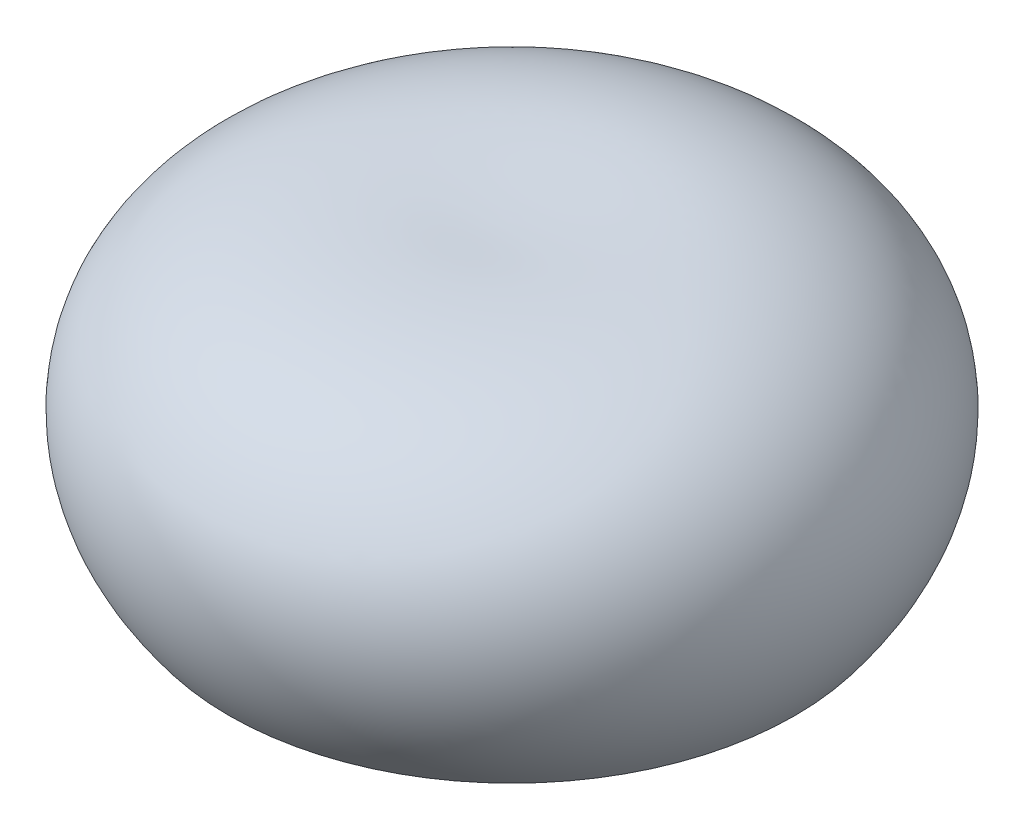
SolidWorks part; units mm, degrees
ref_plane "前视基准面" through (0, 0, 0) normal (0, 0, 1) x (1, 0, 0)
ref_plane "上视基准面" through (0, 0, 0) normal (0, 1, 0) x (1, 0, 0)
ref_plane "右视基准面" through (0, 0, 0) normal (1, 0, 0) x (0, 0, -1)
curve "曲线1"
  spline degree 3 poles (0, 7, 0) (0.0738, 6.9996, 0) (0.1783, 6.9991, 0) (0.3064, 7.0012, 0) (0.3805, 7.0029, 0) (0.4416, 7.0045, 0) (0.495, 7.0061, 0) (0.5432, 7.0077, 0) (0.5875, 7.0093, 0) (0.6288, 7.0109, 0) (0.6676, 7.0125, 0) (0.7044, 7.0141, 0) (0.7394, 7.0157, 0) (0.7729, 7.0172, 0) (0.8051, 7.0187, 0) (0.8362, 7.0203, 0) (0.8662, 7.0218, 0) (0.8953, 7.0233, 0) (0.9235, 7.0247, 0) (0.951, 7.0262, 0) (0.9778, 7.0276, 0) (1.004, 7.0291, 0) (1.0295, 7.0305, 0) (1.0545, 7.0319, 0) (1.079, 7.0333, 0) (1.103, 7.0346, 0) (1.1265, 7.036, 0) (1.1496, 7.0373, 0) (1.1724, 7.0386, 0) (1.1947, 7.0399, 0) (1.2167, 7.0412, 0) (1.2384, 7.0425, 0) (1.2598, 7.0438, 0) (1.2808, 7.045, 0) (1.3016, 7.0462, 0) (1.3221, 7.0474, 0) (1.3423, 7.0486, 0) (1.3623, 7.0498, 0) (1.382, 7.051, 0) (1.4015, 7.0521, 0) (1.4208, 7.0533, 0) (1.4399, 7.0544, 0) (1.4588, 7.0555, 0) (1.4775, 7.0566, 0) (1.496, 7.0577, 0) (1.5143, 7.0587, 0) (1.5324, 7.0598, 0) (1.5504, 7.0608, 0) (1.5682, 7.0618, 0) (1.5859, 7.0628, 0) (1.6034, 7.0638, 0) (1.6207, 7.0648, 0) (1.6379, 7.0657, 0) (1.655, 7.0667, 0) (1.672, 7.0676, 0) (1.6888, 7.0685, 0) (1.7054, 7.0694, 0) (1.722, 7.0703, 0) (1.7385, 7.0712, 0) (1.7548, 7.072, 0) (1.771, 7.0728, 0) (1.7871, 7.0737, 0) (1.8031, 7.0745, 0) (1.819, 7.0753, 0) (1.8348, 7.0761, 0) (1.8505, 7.0768, 0) (1.8661, 7.0776, 0) (1.8816, 7.0783, 0) (1.897, 7.079, 0) (1.9123, 7.0797, 0) (1.9275, 7.0804, 0) (1.9427, 7.0811, 0) (1.9578, 7.0818, 0) (1.9727, 7.0824, 0) (1.9876, 7.0831, 0) (2.0025, 7.0837, 0) (2.0172, 7.0843, 0) (2.0319, 7.0849, 0) (2.0465, 7.0855, 0) (2.061, 7.0861, 0) (2.0755, 7.0866, 0) (2.0899, 7.0872, 0) (2.1042, 7.0877, 0) (2.1184, 7.0882, 0) (2.1326, 7.0887, 0) (2.1468, 7.0892, 0) (2.1608, 7.0896, 0) (2.1748, 7.0901, 0) (2.1888, 7.0905, 0) (2.2027, 7.091, 0) (2.2165, 7.0914, 0) (2.2302, 7.0918, 0) (2.244, 7.0922, 0) (2.2576, 7.0925, 0) (2.2712, 7.0929, 0) (2.2848, 7.0933, 0) (2.2983, 7.0936, 0) (2.3117, 7.0939, 0) (2.3251, 7.0942, 0) (2.3385, 7.0945, 0) (2.3518, 7.0948, 0) (2.365, 7.095, 0) (2.3782, 7.0953, 0) (2.3914, 7.0955, 0) (2.4045, 7.0958, 0) (2.4175, 7.096, 0) (2.4305, 7.0962, 0) (2.4435, 7.0964, 0) (2.4565, 7.0965, 0) (2.4693, 7.0967, 0) (2.4822, 7.0968, 0) (2.495, 7.097, 0) (2.5078, 7.0971, 0) (2.5205, 7.0972, 0) (2.5332, 7.0973, 0) (2.5458, 7.0974, 0) (2.5584, 7.0974, 0) (2.571, 7.0975, 0) (2.5835, 7.0975, 0) (2.596, 7.0975, 0) (2.6085, 7.0975, 0) (2.6209, 7.0975, 0) (2.6333, 7.0975, 0) (2.6457, 7.0975, 0) (2.658, 7.0975, 0) (2.6703, 7.0974, 0) (2.6825, 7.0973, 0) (2.6948, 7.0973, 0) (2.7069, 7.0972, 0) (2.7191, 7.0971, 0) (2.7312, 7.0969, 0) (2.7433, 7.0968, 0) (2.7554, 7.0967, 0) (2.7674, 7.0965, 0) (2.7794, 7.0963, 0) (2.7914, 7.0962, 0) (2.8033, 7.096, 0) (2.8152, 7.0958, 0) (2.8271, 7.0955, 0) (2.8389, 7.0953, 0) (2.8508, 7.095, 0) (2.8625, 7.0948, 0) (2.8743, 7.0945, 0) (2.8861, 7.0942, 0) (2.8978, 7.0939, 0) (2.9094, 7.0936, 0) (2.9211, 7.0933, 0) (2.9327, 7.093, 0) (2.9443, 7.0926, 0) (2.9559, 7.0922, 0) (2.9675, 7.0919, 0) (2.979, 7.0915, 0) (2.9905, 7.0911, 0) (3.002, 7.0907, 0) (3.0134, 7.0902, 0) (3.0249, 7.0898, 0) (3.0363, 7.0893, 0) (3.0477, 7.0889, 0) (3.059, 7.0884, 0) (3.0704, 7.0879, 0) (3.0817, 7.0874, 0) (3.093, 7.0869, 0) (3.1042, 7.0864, 0) (3.1155, 7.0858, 0) (3.1267, 7.0853, 0) (3.1379, 7.0847, 0) (3.1491, 7.0841, 0) (3.1602, 7.0835, 0) (3.1714, 7.0829, 0) (3.1825, 7.0823, 0) (3.1936, 7.0817, 0) (3.2047, 7.0811, 0) (3.2157, 7.0804, 0) (3.2267, 7.0797, 0) (3.2378, 7.0791, 0) (3.2488, 7.0784, 0) (3.2597, 7.0777, 0) (3.2707, 7.0769, 0) (3.2816, 7.0762, 0) (3.2925, 7.0755, 0) (3.3034, 7.0747, 0) (3.3143, 7.074, 0) (3.3252, 7.0732, 0) (3.336, 7.0724, 0) (3.3468, 7.0716, 0) (3.3576, 7.0708, 0) (3.3684, 7.0699, 0) (3.3792, 7.0691, 0) (3.3899, 7.0683, 0) (3.4006, 7.0674, 0) (3.4113, 7.0665, 0) (3.422, 7.0656, 0) (3.4327, 7.0647, 0) (3.4434, 7.0638, 0) (3.454, 7.0629, 0) (3.4646, 7.0619, 0) (3.4752, 7.061, 0) (3.4858, 7.06, 0) (3.4964, 7.059, 0) (3.507, 7.0581, 0) (3.5175, 7.0571, 0) (3.528, 7.056, 0) (3.5385, 7.055, 0) (3.549, 7.054, 0) (3.5595, 7.0529, 0) (3.5699, 7.0519, 0) (3.5804, 7.0508, 0) (3.5908, 7.0497, 0) (3.6012, 7.0486, 0) (3.6116, 7.0475, 0) (3.622, 7.0464, 0) (3.6324, 7.0452, 0) (3.6427, 7.0441, 0) (3.6531, 7.0429, 0) (3.6634, 7.0417, 0) (3.6737, 7.0406, 0) (3.684, 7.0394, 0) (3.6942, 7.0381, 0) (3.7045, 7.0369, 0) (3.7148, 7.0357, 0) (3.725, 7.0344, 0) (3.7352, 7.0332, 0) (3.7454, 7.0319, 0) (3.7556, 7.0306, 0) (3.7658, 7.0293, 0) (3.7759, 7.028, 0) (3.7861, 7.0267, 0) (3.7962, 7.0254, 0) (3.8063, 7.024, 0) (3.8164, 7.0227, 0) (3.8265, 7.0213, 0) (3.8366, 7.0199, 0) (3.8467, 7.0185, 0) (3.8567, 7.0171, 0) (3.8668, 7.0157, 0) (3.8768, 7.0142, 0) (3.8868, 7.0128, 0) (3.8968, 7.0113, 0) (3.9068, 7.0099, 0) (3.9168, 7.0084, 0) (3.9267, 7.0069, 0) (3.9367, 7.0054, 0) (3.9466, 7.0039, 0) (3.9565, 7.0024, 0) (3.9665, 7.0008, 0) (3.9764, 6.9993, 0) (3.9862, 6.9977, 0) (3.9961, 6.9961, 0) (4.006, 6.9945, 0) (4.0158, 6.9929, 0) (4.0257, 6.9913, 0) (4.0355, 6.9897, 0) (4.0453, 6.988, 0) (4.0551, 6.9864, 0) (4.0649, 6.9847, 0) (4.0747, 6.983, 0) (4.0844, 6.9813, 0) (4.0942, 6.9796, 0) (4.1039, 6.9779, 0) (4.1136, 6.9762, 0) (4.1234, 6.9745, 0) (4.1331, 6.9727, 0) (4.1428, 6.971, 0) (4.1524, 6.9692, 0) (4.1621, 6.9674, 0) (4.1718, 6.9656, 0) (4.1814, 6.9638, 0) (4.1911, 6.962, 0) (4.2007, 6.9601, 0) (4.2103, 6.9583, 0) (4.2199, 6.9564, 0) (4.2295, 6.9545, 0) (4.2391, 6.9527, 0) (4.2486, 6.9508, 0) (4.2582, 6.9488, 0) (4.2677, 6.9469, 0) (4.2773, 6.945, 0) (4.2868, 6.943, 0) (4.2963, 6.9411, 0) (4.3058, 6.9391, 0) (4.3153, 6.9371, 0) (4.3248, 6.9351, 0) (4.3343, 6.9331, 0) (4.3437, 6.9311, 0) (4.3532, 6.9291, 0) (4.3626, 6.927, 0) (4.3721, 6.925, 0) (4.3815, 6.9229, 0) (4.3909, 6.9208, 0) (4.4003, 6.9187, 0) (4.4097, 6.9166, 0) (4.4191, 6.9145, 0) (4.4284, 6.9123, 0) (4.4378, 6.9102, 0) (4.4471, 6.908, 0) (4.4565, 6.9059, 0) (4.4658, 6.9037, 0) (4.4751, 6.9015, 0) (4.4844, 6.8993, 0) (4.4937, 6.8971, 0) (4.503, 6.8948, 0) (4.5123, 6.8926, 0) (4.5215, 6.8903, 0) (4.5308, 6.8881, 0) (4.54, 6.8858, 0) (4.5493, 6.8835, 0) (4.5585, 6.8812, 0) (4.5677, 6.8789, 0) (4.5769, 6.8765, 0) (4.5861, 6.8742, 0) (4.5953, 6.8718, 0) (4.6045, 6.8695, 0) (4.6136, 6.8671, 0) (4.6228, 6.8647, 0) (4.6319, 6.8623, 0) (4.6411, 6.8599, 0) (4.6502, 6.8575, 0) (4.6593, 6.855, 0) (4.6684, 6.8526, 0) (4.6775, 6.8501, 0) (4.6866, 6.8476, 0) (4.6957, 6.8451, 0) (4.7048, 6.8426, 0) (4.7138, 6.8401, 0) (4.7229, 6.8376, 0) (4.7319, 6.835, 0) (4.741, 6.8325, 0) (4.75, 6.8299, 0) (4.759, 6.8273, 0) (4.768, 6.8247, 0) (4.777, 6.8221, 0) (4.786, 6.8195, 0) (4.795, 6.8169, 0) (4.8039, 6.8142, 0) (4.8129, 6.8116, 0) (4.8218, 6.8089, 0) (4.8308, 6.8062, 0) (4.8397, 6.8035, 0) (4.8486, 6.8008, 0) (4.8575, 6.7981, 0) (4.8664, 6.7954, 0) (4.8753, 6.7926, 0) (4.8842, 6.7899, 0) (4.8931, 6.7871, 0) (4.902, 6.7843, 0) (4.9108, 6.7815, 0) (4.9197, 6.7787, 0) (4.9285, 6.7759, 0) (4.9373, 6.7731, 0) (4.9462, 6.7702, 0) (4.955, 6.7673, 0) (4.9638, 6.7645, 0) (4.9726, 6.7616, 0) (4.9813, 6.7587, 0) (4.9901, 6.7558, 0) (4.9989, 6.7529, 0) (5.0076, 6.7499, 0) (5.0164, 6.747, 0) (5.0251, 6.744, 0) (5.0339, 6.7411, 0) (5.0426, 6.7381, 0) (5.0513, 6.7351, 0) (5.06, 6.7321, 0) (5.0687, 6.729, 0) (5.0774, 6.726, 0) (5.0861, 6.7229, 0) (5.0947, 6.7199, 0) (5.1034, 6.7168, 0) (5.112, 6.7137, 0) (5.1207, 6.7106, 0) (5.1293, 6.7075, 0) (5.1379, 6.7044, 0) (5.1465, 6.7012, 0) (5.1552, 6.6981, 0) (5.1638, 6.6949, 0) (5.1723, 6.6917, 0) (5.1809, 6.6885, 0) (5.1895, 6.6853, 0) (5.1981, 6.6821, 0) (5.2066, 6.6789, 0) (5.2151, 6.6756, 0) (5.2237, 6.6724, 0) (5.2322, 6.6691, 0) (5.2407, 6.6658, 0) (5.2492, 6.6625, 0) (5.2577, 6.6592, 0) (5.2662, 6.6559, 0) (5.2747, 6.6526, 0) (5.2832, 6.6492, 0) (5.2917, 6.6459, 0) (5.3001, 6.6425, 0) (5.3086, 6.6391, 0) (5.317, 6.6357, 0) (5.3254, 6.6323, 0) (5.3338, 6.6289, 0) (5.3423, 6.6254, 0) (5.3507, 6.622, 0) (5.3591, 6.6185, 0) (5.3674, 6.615, 0) (5.3758, 6.6115, 0) (5.3842, 6.608, 0) (5.3926, 6.6045, 0) (5.4009, 6.601, 0) (5.4092, 6.5974, 0) (5.4176, 6.5939, 0) (5.4259, 6.5903, 0) (5.4342, 6.5867, 0) (5.4425, 6.5831, 0) (5.4508, 6.5795, 0) (5.4591, 6.5759, 0) (5.4674, 6.5722, 0) (5.4757, 6.5686, 0) (5.4839, 6.5649, 0) (5.4922, 6.5612, 0) (5.5004, 6.5576, 0) (5.5087, 6.5538, 0) (5.5169, 6.5501, 0) (5.5251, 6.5464, 0) (5.5333, 6.5427, 0) (5.5415, 6.5389, 0) (5.5497, 6.5351, 0) (5.5579, 6.5313, 0) (5.5661, 6.5275, 0) (5.5743, 6.5237, 0) (5.5824, 6.5199, 0) (5.5906, 6.5161, 0) (5.5987, 6.5122, 0) (5.6069, 6.5083, 0) (5.615, 6.5045, 0) (5.6231, 6.5006, 0) (5.6312, 6.4967, 0) (5.6393, 6.4927, 0) (5.6474, 6.4888, 0) (5.6555, 6.4849, 0) (5.6635, 6.4809, 0) (5.6716, 6.4769, 0) (5.6796, 6.4729, 0) (5.6877, 6.4689, 0) (5.6957, 6.4649, 0) (5.7038, 6.4609, 0) (5.7118, 6.4568, 0) (5.7198, 6.4528, 0) (5.7278, 6.4487, 0) (5.7358, 6.4446, 0) (5.7438, 6.4405, 0) (5.7517, 6.4364, 0) (5.7597, 6.4323, 0) (5.7676, 6.4282, 0) (5.7756, 6.424, 0) (5.7835, 6.4198, 0) (5.7915, 6.4157, 0) (5.7994, 6.4115, 0) (5.8073, 6.4073, 0) (5.8152, 6.403, 0) (5.8231, 6.3988, 0) (5.831, 6.3945, 0) (5.8388, 6.3903, 0) (5.8467, 6.386, 0) (5.8546, 6.3817, 0) (5.8624, 6.3774, 0) (5.8703, 6.3731, 0) (5.8781, 6.3687, 0) (5.8859, 6.3644, 0) (5.8937, 6.36, 0) (5.9015, 6.3557, 0) (5.9093, 6.3513, 0) (5.9171, 6.3469, 0) (5.9249, 6.3424, 0) (5.9326, 6.338, 0) (5.9404, 6.3336, 0) (5.9481, 6.3291, 0) (5.9559, 6.3246, 0) (5.9636, 6.3201, 0) (5.9713, 6.3156, 0) (5.979, 6.3111, 0) (5.9867, 6.3066, 0) (5.9944, 6.302, 0) (6.0021, 6.2975, 0) (6.0098, 6.2929, 0) (6.0175, 6.2883, 0) (6.0251, 6.2837, 0) (6.0328, 6.2791, 0) (6.0404, 6.2745, 0) (6.048, 6.2698, 0) (6.0556, 6.2652, 0) (6.0633, 6.2605, 0) (6.0709, 6.2558, 0) (6.0784, 6.2511, 0) (6.086, 6.2464, 0) (6.0936, 6.2416, 0) (6.1012, 6.2369, 0) (6.1087, 6.2321, 0) (6.1163, 6.2274, 0) (6.1238, 6.2226, 0) (6.1313, 6.2178, 0) (6.1388, 6.2129, 0) (6.1463, 6.2081, 0) (6.1538, 6.2033, 0) (6.1613, 6.1984, 0) (6.1688, 6.1935, 0) (6.1763, 6.1886, 0) (6.1837, 6.1837, 0) (6.1912, 6.1788, 0) (6.1986, 6.1739, 0) (6.206, 6.1689, 0) (6.2134, 6.1639, 0) (6.2208, 6.159, 0) (6.2282, 6.154, 0) (6.2356, 6.1489, 0) (6.243, 6.1439, 0) (6.2504, 6.1389, 0) (6.2577, 6.1338, 0) (6.2651, 6.1287, 0) (6.2724, 6.1237, 0) (6.2798, 6.1186, 0) (6.2871, 6.1134, 0) (6.2944, 6.1083, 0) (6.3017, 6.1032, 0) (6.309, 6.098, 0) (6.3163, 6.0928, 0) (6.3235, 6.0876, 0) (6.3308, 6.0824, 0) (6.3381, 6.0772, 0) (6.3453, 6.072, 0) (6.3525, 6.0667, 0) (6.3598, 6.0615, 0) (6.367, 6.0562, 0) (6.3742, 6.0509, 0) (6.3814, 6.0456, 0) (6.3885, 6.0403, 0) (6.3957, 6.0349, 0) (6.4029, 6.0296, 0) (6.41, 6.0242, 0) (6.4172, 6.0188, 0) (6.4243, 6.0134, 0) (6.4314, 6.008, 0) (6.4385, 6.0025, 0) (6.4456, 5.9971, 0) (6.4527, 5.9916, 0) (6.4598, 5.9861, 0) (6.4668, 5.9806, 0) (6.4739, 5.9751, 0) (6.4809, 5.9696, 0) (6.488, 5.9641, 0) (6.495, 5.9585, 0) (6.502, 5.9529, 0) (6.509, 5.9473, 0) (6.516, 5.9417, 0) (6.523, 5.9361, 0) (6.53, 5.9305, 0) (6.5369, 5.9248, 0) (6.5439, 5.9192, 0) (6.5508, 5.9135, 0) (6.5578, 5.9078, 0) (6.5647, 5.9021, 0) (6.5716, 5.8963, 0) (6.5785, 5.8906, 0) (6.5854, 5.8848, 0) (6.5922, 5.8791, 0) (6.5991, 5.8733, 0) (6.606, 5.8675, 0) (6.6128, 5.8616, 0) (6.6196, 5.8558, 0) (6.6265, 5.8499, 0) (6.6333, 5.8441, 0) (6.6401, 5.8382, 0) (6.6469, 5.8323, 0) (6.6536, 5.8263, 0) (6.6604, 5.8204, 0) (6.6672, 5.8144, 0) (6.6739, 5.8085, 0) (6.6806, 5.8025, 0) (6.6874, 5.7965, 0) (6.6941, 5.7905, 0) (6.7008, 5.7844, 0) (6.7074, 5.7784, 0) (6.7141, 5.7723, 0) (6.7208, 5.7662, 0) (6.7274, 5.7601, 0) (6.7341, 5.754, 0) (6.7407, 5.7479, 0) (6.7473, 5.7417, 0) (6.7539, 5.7356, 0) (6.7605, 5.7294, 0) (6.7671, 5.7232, 0) (6.7737, 5.717, 0) (6.7802, 5.7107, 0) (6.7868, 5.7045, 0) (6.7933, 5.6982, 0) (6.7998, 5.6919, 0) (6.8064, 5.6856, 0) (6.8129, 5.6793, 0) (6.8194, 5.673, 0) (6.8258, 5.6666, 0) (6.8323, 5.6603, 0) (6.8387, 5.6539, 0) (6.8452, 5.6475, 0) (6.8516, 5.6411, 0) (6.858, 5.6346, 0) (6.8644, 5.6282, 0) (6.8708, 5.6217, 0) (6.8772, 5.6152, 0) (6.8836, 5.6087, 0) (6.8899, 5.6022, 0) (6.8963, 5.5957, 0) (6.9026, 5.5891, 0) (6.9089, 5.5825, 0) (6.9152, 5.5759, 0) (6.9215, 5.5693, 0) (6.9278, 5.5627, 0) (6.9341, 5.5561, 0) (6.9403, 5.5494, 0) (6.9466, 5.5427, 0) (6.9528, 5.5361, 0) (6.959, 5.5293, 0) (6.9652, 5.5226, 0) (6.9714, 5.5159, 0) (6.9776, 5.5091, 0) (6.9838, 5.5023, 0) (6.9899, 5.4955, 0) (6.9961, 5.4887, 0) (7.0022, 5.4819, 0) (7.0083, 5.475, 0) (7.0144, 5.4682, 0) (7.0205, 5.4613, 0) (7.0266, 5.4544, 0) (7.0326, 5.4475, 0) (7.0387, 5.4405, 0) (7.0447, 5.4336, 0) (7.0507, 5.4266, 0) (7.0568, 5.4196, 0) (7.0627, 5.4126, 0) (7.0687, 5.4055, 0) (7.0747, 5.3985, 0) (7.0807, 5.3914, 0) (7.0866, 5.3844, 0) (7.0925, 5.3772, 0) (7.0984, 5.3701, 0) (7.1043, 5.363, 0) (7.1102, 5.3558, 0) (7.1161, 5.3487, 0) (7.122, 5.3415, 0) (7.1278, 5.3343, 0) (7.1336, 5.327, 0) (7.1395, 5.3198, 0) (7.1453, 5.3125, 0) (7.151, 5.3052, 0) (7.1568, 5.2979, 0) (7.1626, 5.2906, 0) (7.1683, 5.2833, 0) (7.1741, 5.2759, 0) (7.1798, 5.2685, 0) (7.1855, 5.2611, 0) (7.1912, 5.2537, 0) (7.1968, 5.2463, 0) (7.2025, 5.2388, 0) (7.2082, 5.2313, 0) (7.2138, 5.2238, 0) (7.2194, 5.2163, 0) (7.225, 5.2088, 0) (7.2306, 5.2013, 0) (7.2362, 5.1937, 0) (7.2417, 5.1861, 0) (7.2473, 5.1785, 0) (7.2528, 5.1709, 0) (7.2583, 5.1632, 0) (7.2638, 5.1556, 0) (7.2693, 5.1479, 0) (7.2748, 5.1402, 0) (7.2802, 5.1324, 0) (7.2856, 5.1247, 0) (7.2911, 5.1169, 0) (7.2965, 5.1092, 0) (7.3019, 5.1014, 0) (7.3072, 5.0935, 0) (7.3126, 5.0857, 0) (7.3179, 5.0778, 0) (7.3233, 5.0699, 0) (7.3286, 5.062, 0) (7.3339, 5.0541, 0) (7.3391, 5.0462, 0) (7.3444, 5.0382, 0) (7.3497, 5.0302, 0) (7.3549, 5.0222, 0) (7.3601, 5.0142, 0) (7.3653, 5.0062, 0) (7.3705, 4.9981, 0) (7.3757, 4.99, 0) (7.3808, 4.9819, 0) (7.3859, 4.9738, 0) (7.3911, 4.9657, 0) (7.3962, 4.9575, 0) (7.4012, 4.9493, 0) (7.4063, 4.9411, 0) (7.4114, 4.9329, 0) (7.4164, 4.9246, 0) (7.4214, 4.9164, 0) (7.4264, 4.9081, 0) (7.4314, 4.8998, 0) (7.4364, 4.8914, 0) (7.4413, 4.8831, 0) (7.4462, 4.8747, 0) (7.4512, 4.8663, 0) (7.4561, 4.8579, 0) (7.4609, 4.8495, 0) (7.4658, 4.841, 0) (7.4706, 4.8325, 0) (7.4755, 4.824, 0) (7.4803, 4.8155, 0) (7.4851, 4.807, 0) (7.4899, 4.7984, 0) (7.4946, 4.7898, 0) (7.4993, 4.7812, 0) (7.5041, 4.7726, 0) (7.5088, 4.7639, 0) (7.5134, 4.7552, 0) (7.5181, 4.7465, 0) (7.5228, 4.7378, 0) (7.5274, 4.7291, 0) (7.532, 4.7203, 0) (7.5366, 4.7115, 0) (7.5412, 4.7027, 0) (7.5457, 4.6939, 0) (7.5503, 4.6851, 0) (7.5548, 4.6762, 0) (7.5593, 4.6673, 0) (7.5637, 4.6584, 0) (7.5682, 4.6494, 0) (7.5726, 4.6405, 0) (7.5771, 4.6315, 0) (7.5815, 4.6225, 0) (7.5858, 4.6134, 0) (7.5902, 4.6044, 0) (7.5945, 4.5953, 0) (7.5989, 4.5862, 0) (7.6032, 4.5771, 0) (7.6075, 4.5679, 0) (7.6117, 4.5587, 0) (7.616, 4.5495, 0) (7.6202, 4.5403, 0) (7.6244, 4.5311, 0) (7.6286, 4.5218, 0) (7.6327, 4.5125, 0) (7.6369, 4.5032, 0) (7.641, 4.4939, 0) (7.6451, 4.4845, 0) (7.6492, 4.4751, 0) (7.6532, 4.4657, 0) (7.6573, 4.4563, 0) (7.6613, 4.4468, 0) (7.6653, 4.4373, 0) (7.6692, 4.4278, 0) (7.6732, 4.4183, 0) (7.6771, 4.4087, 0) (7.681, 4.3992, 0) (7.6849, 4.3896, 0) (7.6888, 4.3799, 0) (7.6926, 4.3703, 0) (7.6964, 4.3606, 0) (7.7002, 4.3509, 0) (7.704, 4.3411, 0) (7.7078, 4.3314, 0) (7.7115, 4.3216, 0) (7.7152, 4.3118, 0) (7.7189, 4.302, 0) (7.7226, 4.2921, 0) (7.7262, 4.2822, 0) (7.7298, 4.2723, 0) (7.7334, 4.2624, 0) (7.737, 4.2524, 0) (7.7405, 4.2424, 0) (7.744, 4.2324, 0) (7.7475, 4.2223, 0) (7.751, 4.2123, 0) (7.7545, 4.2022, 0) (7.7579, 4.1921, 0) (7.7613, 4.1819, 0) (7.7647, 4.1717, 0) (7.768, 4.1615, 0) (7.7714, 4.1513, 0) (7.7747, 4.141, 0) (7.778, 4.1308, 0) (7.7812, 4.1204, 0) (7.7845, 4.1101, 0) (7.7877, 4.0997, 0) (7.7908, 4.0893, 0) (7.794, 4.0789, 0) (7.7971, 4.0685, 0) (7.8002, 4.058, 0) (7.8033, 4.0475, 0) (7.8064, 4.0369, 0) (7.8094, 4.0264, 0) (7.8124, 4.0158, 0) (7.8154, 4.0051, 0) (7.8183, 3.9945, 0) (7.8212, 3.9838, 0) (7.8241, 3.9731, 0) (7.827, 3.9624, 0) (7.8298, 3.9516, 0) (7.8327, 3.9408, 0) (7.8354, 3.93, 0) (7.8382, 3.9191, 0) (7.8409, 3.9082, 0) (7.8436, 3.8973, 0) (7.8463, 3.8863, 0) (7.849, 3.8754, 0) (7.8516, 3.8643, 0) (7.8542, 3.8533, 0) (7.8567, 3.8422, 0) (7.8593, 3.8311, 0) (7.8618, 3.82, 0) (7.8642, 3.8088, 0) (7.8667, 3.7976, 0) (7.8691, 3.7864, 0) (7.8715, 3.7751, 0) (7.8738, 3.7638, 0) (7.8762, 3.7525, 0) (7.8785, 3.7411, 0) (7.8807, 3.7297, 0) (7.883, 3.7183, 0) (7.8852, 3.7069, 0) (7.8873, 3.6954, 0) (7.8895, 3.6838, 0) (7.8916, 3.6723, 0) (7.8937, 3.6607, 0) (7.8957, 3.6491, 0) (7.8977, 3.6374, 0) (7.8997, 3.6257, 0) (7.9016, 3.614, 0) (7.9036, 3.6022, 0) (7.9054, 3.5904, 0) (7.9073, 3.5786, 0) (7.9091, 3.5667, 0) (7.9109, 3.5548, 0) (7.9126, 3.5429, 0) (7.9144, 3.5309, 0) (7.916, 3.5189, 0) (7.9177, 3.5068, 0) (7.9193, 3.4947, 0) (7.9209, 3.4826, 0) (7.9224, 3.4705, 0) (7.9239, 3.4583, 0) (7.9254, 3.446, 0) (7.9268, 3.4338, 0) (7.9282, 3.4214, 0) (7.9296, 3.4091, 0) (7.9309, 3.3967, 0) (7.9322, 3.3843, 0) (7.9334, 3.3718, 0) (7.9346, 3.3593, 0) (7.9358, 3.3468, 0) (7.9369, 3.3342, 0) (7.938, 3.3215, 0) (7.9391, 3.3089, 0) (7.9401, 3.2962, 0) (7.9411, 3.2834, 0) (7.942, 3.2706, 0) (7.9429, 3.2578, 0) (7.9438, 3.2449, 0) (7.9446, 3.232, 0) (7.9454, 3.219, 0) (7.9461, 3.206, 0) (7.9468, 3.193, 0) (7.9475, 3.1799, 0) (7.9481, 3.1668, 0) (7.9486, 3.1536, 0) (7.9492, 3.1403, 0) (7.9496, 3.1271, 0) (7.9501, 3.1138, 0) (7.9505, 3.1004, 0) (7.9508, 3.087, 0) (7.9511, 3.0735, 0) (7.9514, 3.06, 0) (7.9516, 3.0465, 0) (7.9517, 3.0329, 0) (7.9518, 3.0192, 0) (7.9519, 3.0055, 0) (7.9519, 2.9918, 0) (7.9519, 2.978, 0) (7.9518, 2.9641, 0) (7.9517, 2.9502, 0) (7.9515, 2.9363, 0) (7.9513, 2.9223, 0) (7.951, 2.9082, 0) (7.9507, 2.8941, 0) (7.9503, 2.88, 0) (7.9499, 2.8657, 0) (7.9494, 2.8515, 0) (7.9489, 2.8371, 0) (7.9483, 2.8228, 0) (7.9477, 2.8083, 0) (7.947, 2.7938, 0) (7.9462, 2.7793, 0) (7.9454, 2.7647, 0) (7.9445, 2.75, 0) (7.9436, 2.7353, 0) (7.9426, 2.7205, 0) (7.9416, 2.7056, 0) (7.9405, 2.6907, 0) (7.9393, 2.6757, 0) (7.9381, 2.6607, 0) (7.9368, 2.6456, 0) (7.9355, 2.6304, 0) (7.9341, 2.6152, 0) (7.9326, 2.5999, 0) (7.9311, 2.5845, 0) (7.9295, 2.5691, 0) (7.9278, 2.5536, 0) (7.9261, 2.538, 0) (7.9243, 2.5224, 0) (7.9224, 2.5066, 0) (7.9205, 2.4909, 0) (7.9185, 2.475, 0) (7.9164, 2.459, 0) (7.9143, 2.443, 0) (7.912, 2.4269, 0) (7.9097, 2.4108, 0) (7.9074, 2.3945, 0) (7.9049, 2.3782, 0) (7.9024, 2.3618, 0) (7.8998, 2.3453, 0) (7.8971, 2.3287, 0) (7.8943, 2.312, 0) (7.8915, 2.2953, 0) (7.8885, 2.2784, 0) (7.8855, 2.2615, 0) (7.8824, 2.2445, 0) (7.8792, 2.2273, 0) (7.8759, 2.2101, 0) (7.8725, 2.1928, 0) (7.8691, 2.1754, 0) (7.8655, 2.1579, 0) (7.8618, 2.1403, 0) (7.8581, 2.1225, 0) (7.8542, 2.1047, 0) (7.8503, 2.0868, 0) (7.8462, 2.0687, 0) (7.842, 2.0506, 0) (7.8378, 2.0323, 0) (7.8334, 2.0139, 0) (7.8289, 1.9954, 0) (7.8243, 1.9767, 0) (7.8195, 1.9579, 0) (7.8147, 1.939, 0) (7.8097, 1.92, 0) (7.8046, 1.9008, 0) (7.7994, 1.8815, 0) (7.794, 1.8621, 0) (7.7885, 1.8425, 0) (7.7829, 1.8227, 0) (7.7771, 1.8028, 0) (7.7712, 1.7828, 0) (7.7652, 1.7626, 0) (7.759, 1.7422, 0) (7.7526, 1.7216, 0) (7.7461, 1.7009, 0) (7.7394, 1.6799, 0) (7.7325, 1.6588, 0) (7.7255, 1.6375, 0) (7.7182, 1.616, 0) (7.7108, 1.5943, 0) (7.7032, 1.5723, 0) (7.6954, 1.5502, 0) (7.6874, 1.5278, 0) (7.6792, 1.5051, 0) (7.6708, 1.4822, 0) (7.6621, 1.4591, 0) (7.6532, 1.4357, 0) (7.644, 1.412, 0) (7.6346, 1.388, 0) (7.6249, 1.3637, 0) (7.615, 1.3391, 0) (7.6047, 1.3141, 0) (7.5941, 1.2888, 0) (7.5833, 1.2631, 0) (7.572, 1.237, 0) (7.5604, 1.2105, 0) (7.5485, 1.1835, 0) (7.5361, 1.1561, 0) (7.5233, 1.1282, 0) (7.51, 1.0997, 0) (7.4963, 1.0707, 0) (7.482, 1.041, 0) (7.4672, 1.0107, 0) (7.4518, 0.9797, 0) (7.4357, 0.9478, 0) (7.4189, 0.9152, 0) (7.4013, 0.8815, 0) (7.3829, 0.8469, 0) (7.3635, 0.811, 0) (7.343, 0.7739, 0) (7.3212, 0.7352, 0) (7.2981, 0.6948, 0) (7.2732, 0.6523, 0) (7.2464, 0.6073, 0) (7.2172, 0.5594, 0) (7.1849, 0.5076, 0) (7.1485, 0.4506, 0) (7.1062, 0.386, 0) (7.0539, 0.3086, 0) (6.9626, 0.1779, 0) (6.8856, 0.0734, 0) (6.8314, 0, 0) knots 0 0 0 0 0.016508 0.023364 0.028636 0.033092 0.037026 0.040591 0.043877 0.046942 0.049828 0.052563 0.055171 0.057668 0.060068 0.062382 0.06462 0.066789 0.068896 0.070946 0.072944 0.074894 0.0768 0.078664 0.080491 0.082282 0.08404 0.085766 0.087463 0.089131 0.090774 0.092392 0.093986 0.095557 0.097107 0.098637 0.100147 0.101639 0.103112 0.104569 0.10601 0.107434 0.108844 0.110239 0.11162 0.112987 0.114341 0.115683 0.117013 0.118331 0.119637 0.120933 0.122218 0.123492 0.124757 0.126012 0.127257 0.128493 0.129721 0.130939 0.132149 0.133351 0.134545 0.135731 0.13691 0.138081 0.139245 0.140402 0.141552 0.142695 0.143832 0.144962 0.146086 0.147204 0.148315 0.149421 0.150522 0.151616 0.152705 0.153789 0.154868 0.155941 0.157009 0.158072 0.159131 0.160184 0.161233 0.162277 0.163317 0.164352 0.165383 0.16641 0.167433 0.168451 0.169465 0.170476 0.171482 0.172485 0.173483 0.174478 0.17547 0.176457 0.177442 0.178422 0.1794 0.180374 0.181344 0.182312 0.183276 0.184236 0.185194 0.186149 0.187101 0.188049 0.188995 0.189938 0.190877 0.191815 0.192749 0.19368 0.194609 0.195535 0.196459 0.19738 0.198298 0.199214 0.200127 0.201038 0.201946 0.202852 0.203756 0.204657 0.205556 0.206453 0.207347 0.208239 0.209129 0.210017 0.210902 0.211786 0.212667 0.213547 0.214424 0.215299 0.216172 0.217044 0.217913 0.21878 0.219646 0.220509 0.221371 0.222231 0.223089 0.223945 0.2248 0.225652 0.226503 0.227353 0.2282 0.229046 0.22989 0.230732 0.231573 0.232412 0.23325 0.234086 0.23492 0.235753 0.236585 0.237414 0.238243 0.239069 0.239895 0.240719 0.241541 0.242362 0.243182 0.244 0.244816 0.245632 0.246446 0.247258 0.24807 0.24888 0.249688 0.250496 0.251302 0.252106 0.25291 0.253712 0.254513 0.255313 0.256111 0.256909 0.257705 0.2585 0.259294 0.260086 0.260878 0.261668 0.262457 0.263245 0.264032 0.264818 0.265603 0.266386 0.267169 0.26795 0.268731 0.26951 0.270288 0.271066 0.271842 0.272617 0.273391 0.274165 0.274937 0.275708 0.276478 0.277248 0.278016 0.278784 0.27955 0.280316 0.28108 0.281844 0.282607 0.283369 0.28413 0.28489 0.285649 0.286407 0.287165 0.287921 0.288677 0.289432 0.290186 0.290939 0.291692 0.292444 0.293194 0.293944 0.294693 0.295442 0.296189 0.296936 0.297682 0.298428 0.299172 0.299916 0.300659 0.301401 0.302143 0.302883 0.303624 0.304363 0.305101 0.305839 0.306577 0.307313 0.308049 0.308784 0.309518 0.310252 0.310985 0.311718 0.312449 0.31318 0.313911 0.31464 0.31537 0.316098 0.316826 0.317553 0.31828 0.319006 0.319731 0.320456 0.32118 0.321903 0.322626 0.323349 0.32407 0.324791 0.325512 0.326232 0.326951 0.32767 0.328389 0.329106 0.329824 0.33054 0.331256 0.331972 0.332687 0.333401 0.334115 0.334829 0.335541 0.336254 0.336966 0.337677 0.338388 0.339098 0.339808 0.340517 0.341226 0.341934 0.342642 0.34335 0.344057 0.344763 0.345469 0.346174 0.346879 0.347584 0.348288 0.348992 0.349695 0.350398 0.3511 0.351802 0.352503 0.353204 0.353905 0.354605 0.355305 0.356004 0.356703 0.357401 0.3581 0.358797 0.359494 0.360191 0.360888 0.361584 0.362279 0.362975 0.36367 0.364364 0.365058 0.365752 0.366445 0.367138 0.367831 0.368523 0.369215 0.369907 0.370598 0.371289 0.371979 0.372669 0.373359 0.374049 0.374738 0.375427 0.376115 0.376803 0.377491 0.378178 0.378866 0.379552 0.380239 0.380925 0.381611 0.382297 0.382982 0.383667 0.384351 0.385036 0.38572 0.386404 0.387087 0.38777 0.388453 0.389136 0.389818 0.3905 0.391182 0.391863 0.392545 0.393226 0.393906 0.394587 0.395267 0.395947 0.396627 0.397306 0.397985 0.398664 0.399343 0.400021 0.400699 0.401377 0.402055 0.402733 0.40341 0.404087 0.404764 0.40544 0.406117 0.406793 0.407469 0.408144 0.40882 0.409495 0.41017 0.410845 0.41152 0.412194 0.412868 0.413542 0.414216 0.41489 0.415563 0.416237 0.41691 0.417583 0.418255 0.418928 0.4196 0.420273 0.420945 0.421616 0.422288 0.42296 0.423631 0.424302 0.424973 0.425644 0.426315 0.426986 0.427656 0.428326 0.428997 0.429667 0.430336 0.431006 0.431676 0.432345 0.433015 0.433684 0.434353 0.435022 0.435691 0.436359 0.437028 0.437696 0.438365 0.439033 0.439701 0.440369 0.441037 0.441705 0.442373 0.44304 0.443708 0.444375 0.445043 0.44571 0.446377 0.447044 0.447711 0.448378 0.449045 0.449711 0.450378 0.451045 0.451711 0.452378 0.453044 0.45371 0.454377 0.455043 0.455709 0.456375 0.457041 0.457707 0.458373 0.459039 0.459705 0.460371 0.461036 0.461702 0.462368 0.463034 0.463699 0.464365 0.46503 0.465696 0.466361 0.467027 0.467692 0.468358 0.469023 0.469689 0.470354 0.47102 0.471685 0.472351 0.473016 0.473681 0.474347 0.475012 0.475678 0.476343 0.477009 0.477674 0.47834 0.479005 0.479671 0.480336 0.481002 0.481668 0.482333 0.482999 0.483665 0.48433 0.484996 0.485662 0.486328 0.486994 0.48766 0.488326 0.488992 0.489658 0.490324 0.490991 0.491657 0.492324 0.49299 0.493657 0.494323 0.49499 0.495657 0.496324 0.496991 0.497658 0.498325 0.498992 0.499659 0.500327 0.500994 0.501662 0.50233 0.502997 0.503665 0.504333 0.505001 0.50567 0.506338 0.507007 0.507675 0.508344 0.509013 0.509682 0.510351 0.511021 0.51169 0.51236 0.513029 0.513699 0.514369 0.515039 0.51571 0.51638 0.517051 0.517722 0.518393 0.519064 0.519735 0.520407 0.521078 0.52175 0.522422 0.523095 0.523767 0.52444 0.525113 0.525786 0.526459 0.527132 0.527806 0.52848 0.529154 0.529828 0.530502 0.531177 0.531852 0.532527 0.533203 0.533878 0.534554 0.53523 0.535907 0.536583 0.53726 0.537937 0.538614 0.539292 0.53997 0.540648 0.541327 0.542005 0.542684 0.543363 0.544043 0.544723 0.545403 0.546083 0.546764 0.547445 0.548126 0.548808 0.549489 0.550172 0.550854 0.551537 0.55222 0.552904 0.553587 0.554271 0.554956 0.555641 0.556326 0.557011 0.557697 0.558383 0.55907 0.559757 0.560444 0.561132 0.56182 0.562508 0.563197 0.563886 0.564576 0.565266 0.565956 0.566647 0.567338 0.568029 0.568721 0.569414 0.570107 0.5708 0.571493 0.572188 0.572882 0.573577 0.574272 0.574968 0.575665 0.576361 0.577059 0.577756 0.578454 0.579153 0.579852 0.580552 0.581252 0.581952 0.582653 0.583355 0.584057 0.58476 0.585463 0.586166 0.586871 0.587575 0.58828 0.588986 0.589692 0.590399 0.591107 0.591815 0.592523 0.593232 0.593942 0.594652 0.595363 0.596074 0.596786 0.597499 0.598212 0.598926 0.59964 0.600355 0.601071 0.601787 0.602504 0.603222 0.60394 0.604659 0.605379 0.606099 0.60682 0.607541 0.608264 0.608987 0.60971 0.610435 0.61116 0.611885 0.612612 0.613339 0.614067 0.614796 0.615525 0.616255 0.616986 0.617718 0.61845 0.619183 0.619917 0.620652 0.621388 0.622124 0.622861 0.623599 0.624338 0.625078 0.625818 0.62656 0.627302 0.628045 0.628789 0.629534 0.630279 0.631026 0.631773 0.632522 0.633271 0.634021 0.634772 0.635524 0.636277 0.637031 0.637786 0.638542 0.639299 0.640056 0.640815 0.641575 0.642336 0.643098 0.64386 0.644624 0.645389 0.646155 0.646922 0.64769 0.648459 0.64923 0.650001 0.650773 0.651547 0.652322 0.653098 0.653875 0.654653 0.655432 0.656212 0.656994 0.657777 0.658561 0.659346 0.660133 0.66092 0.661709 0.662499 0.663291 0.664084 0.664878 0.665673 0.66647 0.667268 0.668067 0.668868 0.66967 0.670473 0.671278 0.672084 0.672892 0.673701 0.674511 0.675323 0.676136 0.676951 0.677768 0.678585 0.679405 0.680225 0.681048 0.681872 0.682697 0.683524 0.684353 0.685183 0.686015 0.686849 0.687684 0.688521 0.689359 0.690199 0.691041 0.691885 0.692731 0.693578 0.694427 0.695278 0.69613 0.696985 0.697841 0.698699 0.699559 0.700421 0.701285 0.702151 0.703018 0.703888 0.70476 0.705634 0.706509 0.707387 0.708267 0.709149 0.710033 0.710919 0.711808 0.712698 0.713591 0.714486 0.715384 0.716283 0.717185 0.718089 0.718996 0.719905 0.720816 0.721729 0.722646 0.723564 0.724485 0.725409 0.726335 0.727264 0.728195 0.729129 0.730066 0.731005 0.731947 0.732892 0.733839 0.734789 0.735743 0.736699 0.737658 0.738619 0.739584 0.740552 0.741523 0.742497 0.743474 0.744454 0.745438 0.746424 0.747414 0.748407 0.749404 0.750404 0.751407 0.752414 0.753424 0.754438 0.755455 0.756476 0.757501 0.758529 0.759562 0.760598 0.761638 0.762681 0.763729 0.764781 0.765837 0.766897 0.767962 0.76903 0.770103 0.77118 0.772262 0.773348 0.774439 0.775534 0.776634 0.777739 0.778849 0.779963 0.781083 0.782208 0.783337 0.784472 0.785613 0.786758 0.787909 0.789066 0.790228 0.791396 0.79257 0.79375 0.794936 0.796128 0.797326 0.79853 0.799741 0.800959 0.802183 0.803414 0.804652 0.805897 0.807149 0.808408 0.809675 0.81095 0.812232 0.813522 0.814821 0.816127 0.817442 0.818765 0.820098 0.821439 0.822789 0.824149 0.825518 0.826897 0.828286 0.829685 0.831095 0.832516 0.833947 0.83539 0.836844 0.83831 0.839789 0.841279 0.842783 0.8443 0.84583 0.847375 0.848933 0.850507 0.852096 0.8537 0.855321 0.856959 0.858613 0.860286 0.861977 0.863688 0.865418 0.867169 0.868942 0.870736 0.872554 0.874396 0.876263 0.878157 0.880078 0.882027 0.884007 0.886019 0.888063 0.890143 0.89226 0.894416 0.896614 0.898856 0.901145 0.903484 0.905877 0.908328 0.910841 0.913422 0.916077 0.918813 0.921638 0.924562 0.927596 0.930754 0.934054 0.937517 0.941171 0.945054 0.949215 0.953729 0.958707 0.964338 0.970988 0.979601 1 1 1 1
sketch "草图1" plane through (0, 0, 0) normal (0, 0, 1) x (1, 0, 0)
  line L0 (0, 7) -> (0, 0)
  line L1 (6.8314, 0) -> (0, 0)
  spline S0 degree 3 number of poles 1003 (0, 7) -> (6.8314, 0) construction
  spline S1 degree 3 number of poles 1003 (0, 7) -> (6.8314, 0)
revolve "旋转1" add sketch "草图1" angle 360 about L0
sketch "草图2" plane through (0, 0, 0) normal (0, -1, 0) x (1, 0, 0)
  line L0 (0, 2) -> (0, -2)
  arc A0 (0, -2) -> (0, 2) centre (0, 0) ccw
revolve "切除-旋转1" cut sketch "草图2" angle 360 about L0
